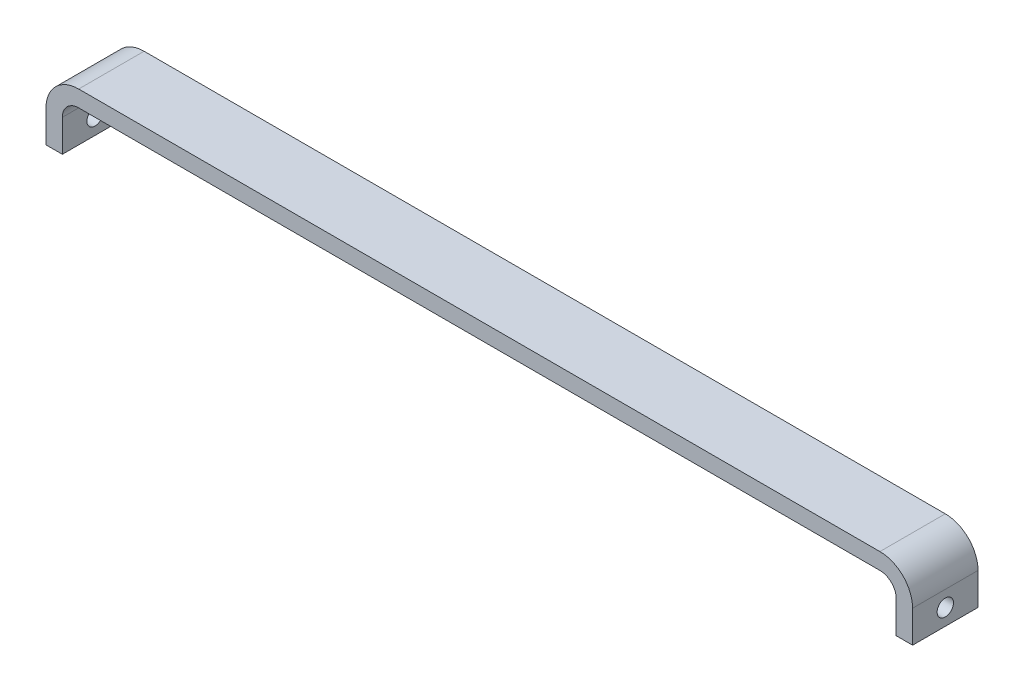
SolidWorks part; units mm, degrees
ref_plane "Front Plane" through (0, 0, 0) normal (0, 0, 1) x (1, 0, 0)
ref_plane "Top Plane" through (0, 0, 0) normal (0, 1, 0) x (1, 0, 0)
ref_plane "Right Plane" through (0, 0, 0) normal (1, 0, 0) x (0, 0, -1)
sketch "Sketch1" plane through (0, 0, 0) normal (0, 0, 1) x (1, 0, 0)
  line L0 (0, 0) -> (0, 19.6)
  line L3 (0, 19.6) -> (20, 19.6) construction
  line L4 (20, 19.6) -> (20, 39.6) construction
  line L5 (0, 0) -> (10, 0)
  line L6 (265, 0) -> (265, 41.1401) construction
  line L7 (20, 39.6) -> (510, 39.6)
  line L8 (530, 0) -> (530, 19.6)
  line L9 (0, 0) -> (10, 0)
  line L10 (20, 29.6) -> (510, 29.6)
  line L12 (10, 19.6) -> (10, 0)
  line L13 (520, 19.6) -> (520, 0)
  line L14 (520, 0) -> (530, 0)
  arc A2 (20, 39.6) -> (0, 19.6) centre (20, 19.6) ccw
  arc A3 (510, 39.6) -> (530, 19.6) centre (510, 19.6) cw
  arc A4 (20, 29.6) -> (10, 19.6) centre (20, 19.6) ccw
  arc A5 (510, 29.6) -> (520, 19.6) centre (510, 19.6) cw
  point P15 (265, 39.6)
  point P19 (265, 29.6)
  dimension "D1" = 19.6
  dimension "D2" = 20
  dimension "D4" = 530
extrude "Boss-Extrude2" add sketch "Sketch1" along normal blind 40 contours L10 A5 L13 L14 L8 A3 L7 A2 L0 L5 L12 A4
sketch "Sketch2" plane through (0, 0, 0) normal (-1, 0, 0) x (0, 0, 1)
  line L0 (40, 0) -> (0, 0) construction
  line L1 (0, 0) -> (0, 19.6) construction
  line L2 (20, 0) -> (20, 42.8019) construction
  circle A0 centre (20, 10) radius 5
  circle A1 centre (20, 10) radius 5
  dimension "D1" = 10
  dimension "D2" = 10
  dimension "D3" = 20
sketch "Sketch3" plane through (0, 0, 0) normal (-1, 0, 0) x (0, 0, 1)
  circle A0 centre (20, 10) radius 5
extrude "Cut-Extrude1" cut sketch "Sketch3" against normal through all
